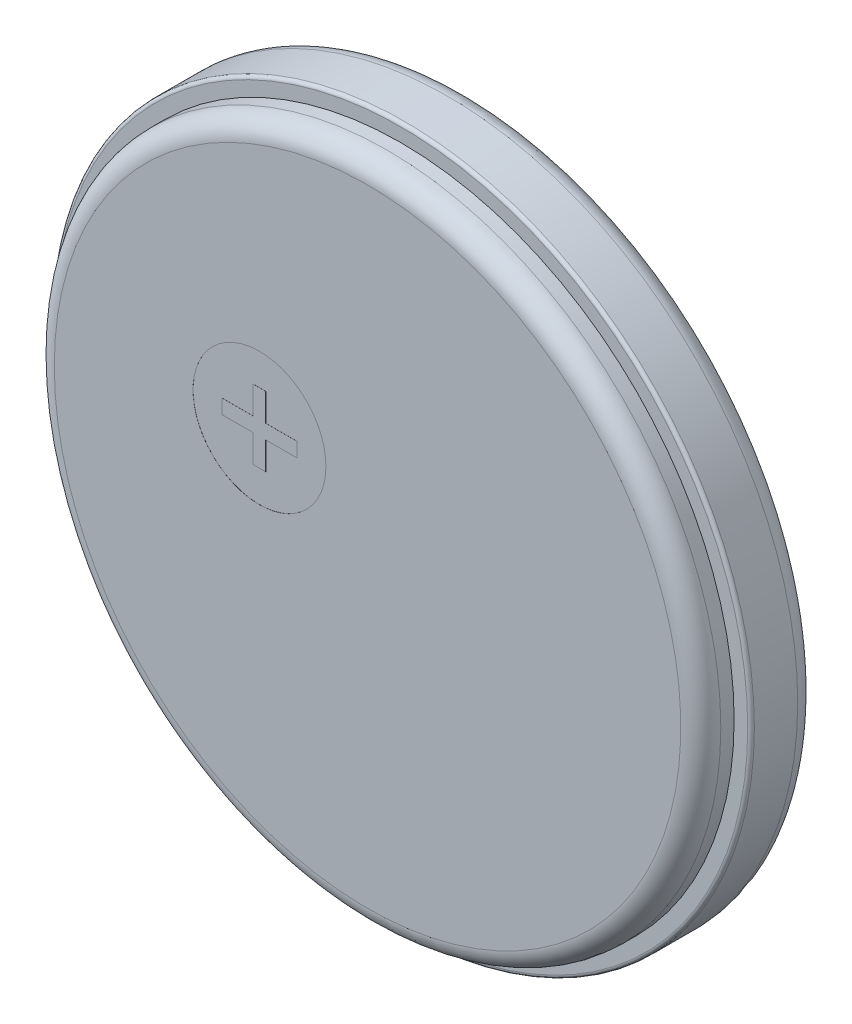
SolidWorks part; units mm, degrees
ref_plane "Front Plane" through (0, 0, 0) normal (0, 0, 1) x (1, 0, 0)
ref_plane "Top Plane" through (0, 0, 0) normal (0, 1, 0) x (1, 0, 0)
ref_plane "Right Plane" through (0, 0, 0) normal (1, 0, 0) x (0, 0, -1)
sketch "Sketch2" plane through (0, 0, 10.668) normal (0, 0, -1) x (-1, 0, 0)
  circle A0 centre (0, 31.75) radius 5
  dimension "D1" = 10
extrude "Boss-Extrude1" add sketch "Sketch2" along normal blind 0.5
fillet "Fillet1" radius 0.3 1 edges at (-5, 31.75, 10.668)
sketch "Sketch3" plane through (0, 0, 10.168) normal (0, 0, -1) x (-1, 0, 0)
  circle A2 centre (0, 31.75) radius 5.254
  circle A3 centre (0, 31.75) radius 5.254
  dimension "D1" = 0.254
extrude "Boss-Extrude2" add sketch "Sketch3" along normal blind 1
fillet "Fillet2" radius 0.3 1 edges at (-5.254, 31.75, 9.168)
fillet "Fillet3" radius 0.05 1 edges at (-5.254, 31.75, 10.168)
sketch "Sketch4" plane through (0, 0, 9.168) normal (0, 0, -1) x (-1, 0, 0)
  line L0 (-2.6501, 29.9289) -> (3.0044, 29.9289) construction
  line L1 (1.1417, 31.9299) -> (0.581, 33.5569)
  line L2 (0.581, 33.5569) -> (0.7228, 33.6419)
  line L3 (0.7228, 33.6419) -> (1.6489, 32.1001)
  line L4 (0.8246, 33.712) -> (1.7515, 32.1672)
  line L5 (0.8246, 33.712) -> (0.9402, 33.7813)
  line L6 (0.9402, 33.7813) -> (2.1566, 32.6492)
  arc A0 (1.6489, 32.1001) -> (1.7515, 32.1672) centre (0.992, 33.2168) ccw
  circle A1 centre (0.581, 33.947) radius 0.2042
  arc A3 (2.1566, 32.6492) -> (1.1417, 31.9299) centre (0.992, 33.2168) ccw
  text T0 "Lithium Ion" font "Impact" height in points 3
extrude "Cut-Extrude1" cut sketch "Sketch4" against normal blind 0.001
sketch "Sketch5" plane through (0, 0, 9.168) normal (0, 0, -1) x (-1, 0, 0)
  text T0 "Veltel" font "堀榘ሲￗ  ⾤" height in points 2
extrude "Cut-Extrude2" cut sketch "Sketch5" against normal blind 0.001
sketch "Sketch6" plane through (0, 0, 9.168) normal (0, 0, -1) x (-1, 0, 0)
  text T0 "CR5505" font "Century Gothic" height in points 2
extrude "Cut-Extrude3" cut sketch "Sketch6" against normal blind 0.001
sketch "Sketch7" plane through (0, 0, 9.168) normal (0, 0, -1) x (-1, 0, 0)
  line L1 (-1.3038, 33.2168) -> (-2.5226, 33.2168)
  line L2 (-1.3038, 33.2168) -> (-1.3038, 33.4152)
  line L3 (-1.3038, 33.4152) -> (-2.5226, 33.4152)
  line L4 (-2.5226, 33.2168) -> (-2.5226, 33.4152)
  line L5 (-1.3038, 33.2168) -> (-2.5226, 33.4152) construction
  line L6 (-1.3038, 33.4152) -> (-2.5226, 33.2168) construction
  circle A0 centre (-1.9132, 33.316) radius 0.8691
  point P0 (-1.9132, 33.316)
extrude "Cut-Extrude4" cut sketch "Sketch7" against normal blind 0.001
sketch "Sketch8" plane through (0, 0, 10.668) normal (0, 0, 1) x (1, 0, 0)
  line L0 (-1.7148, 32.5891) -> (-2.1834, 32.5891)
  line L1 (-1.7148, 31.9585) -> (-1.5276, 31.9585)
  line L2 (-1.7148, 32.5891) -> (-1.7148, 33.0042)
  line L3 (-1.7148, 33.0042) -> (-1.5276, 33.0042)
  line L4 (-1.5276, 31.9585) -> (-1.5276, 32.3736)
  line L5 (-1.7148, 31.9585) -> (-1.5276, 33.0042) construction
  line L6 (-1.7148, 33.0042) -> (-1.5276, 31.9585) construction
  line L7 (-1.059, 32.3736) -> (-1.5276, 32.3736)
  line L8 (-1.059, 32.3736) -> (-1.059, 32.5891)
  line L9 (-1.059, 32.5891) -> (-1.5276, 32.5891)
  line L10 (-2.1834, 32.3736) -> (-2.1834, 32.5891)
  line L11 (-1.059, 32.3736) -> (-2.1834, 32.5891) construction
  line L12 (-1.059, 32.5891) -> (-2.1834, 32.3736) construction
  line L13 (-1.7148, 31.9585) -> (-1.7148, 32.3736)
  line L14 (-1.5276, 32.5891) -> (-1.5276, 33.0042)
  line L16 (-1.7148, 32.3736) -> (-2.1834, 32.3736)
  circle A0 centre (-1.6212, 32.4814) radius 0.9969
  point P0 (-1.6212, 32.4814)
  point P5 (-1.6212, 32.4814)
extrude "Cut-Extrude5" cut sketch "Sketch8" against normal blind 0.001
